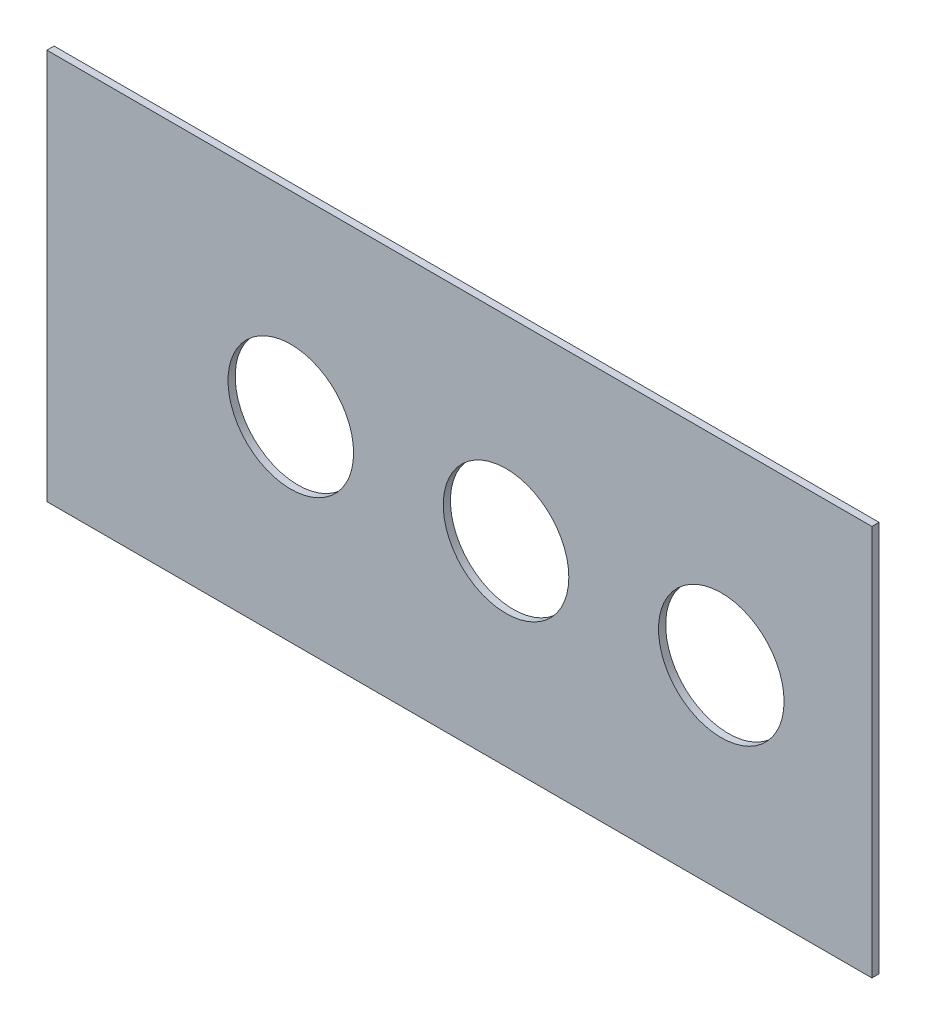
SolidWorks part; units mm, degrees
ref_plane "Front Plane" through (0, 0, 0) normal (0, 0, 1) x (1, 0, 0)
ref_plane "Top Plane" through (0, 0, 0) normal (0, 1, 0) x (1, 0, 0)
ref_plane "Right Plane" through (0, 0, 0) normal (1, 0, 0) x (0, 0, -1)
sketch "Sketch1" plane through (0, 0, 0) normal (0, 0, 1) x (1, 0, 0)
  line L1 (-640, 272.5) -> (510, 272.5)
  line L2 (-640, 272.5) -> (-640, -272.5)
  line L3 (-640, -272.5) -> (510, -272.5)
  line L4 (510, 272.5) -> (510, -272.5)
  circle A0 centre (-300, 0) radius 87.5
  circle A1 centre (0, 0) radius 87.5
  circle A2 centre (300, 0) radius 87.5
  dimension "D5" = 300
  dimension "D7" = 175
  dimension "D8" = 175
  dimension "D9" = 175
  dimension "D1" = 1150
  dimension "D2" = 545
  dimension "D3" = 272.5
  dimension "D6" = 300
extrude "Boss-Extrude1" add sketch "Sketch1" along normal blind 10
